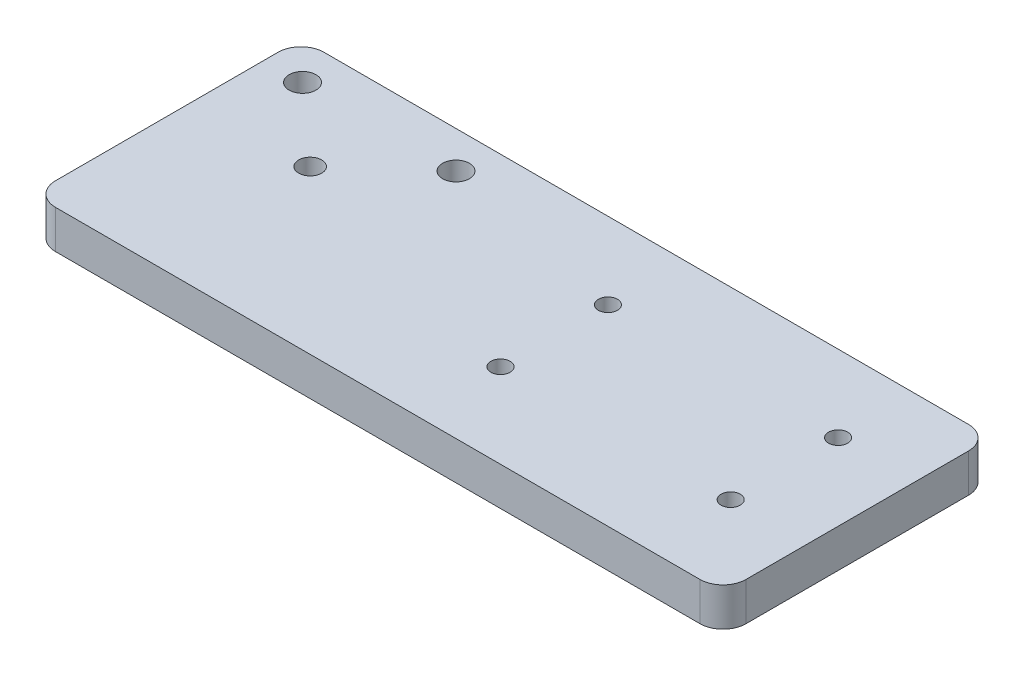
SolidWorks part; units mm, degrees
ref_plane "前视基准面" through (0, 0, 0) normal (0, 0, 1) x (1, 0, 0)
ref_plane "上视基准面" through (0, 0, 0) normal (0, 1, 0) x (1, 0, 0)
ref_plane "右视基准面" through (0, 0, 0) normal (1, 0, 0) x (0, 0, -1)
sketch "草图1" plane through (0, 0, 0) normal (0, 1, 0) x (1, 0, 0)
  line L1 (-45, 17.5) -> (45, 17.5)
  line L2 (-45, 17.5) -> (-45, -17.5)
  line L3 (-45, -17.5) -> (45, -17.5)
  line L4 (45, 17.5) -> (45, -17.5)
  line L5 (-45, 17.5) -> (45, -17.5) construction
  line L6 (-45, -17.5) -> (45, 17.5) construction
  point P0 (0, 0)
  dimension "D1" = 90
  dimension "D2" = 35
extrude "凸台-拉伸1" add sketch "草图1" along normal blind 5 contours L1 L4 L3 L2
sketch "草图2" plane through (0, 5, 0) normal (0, 1, 0) x (1, 0, 0)
  line L0 (45, 17.5) -> (45, -17.5) construction
  line L2 (-45, 17.5) -> (45, 17.5) construction
  circle A0 centre (35, 7.5) radius 1
  dimension "D1" = 2
  dimension "D3" = 10
  dimension "D2" = 10
extrude "切除-拉伸1" cut sketch "草图2" against normal through all
pattern_linear "阵列(线性)1" count 2 spacing 30 along (-1, 0, 0) count 2 spacing 14 along (0, 0, 1) of "切除-拉伸1"
sketch "草图3" plane through (0, 5, 0) normal (0, 1, 0) x (1, 0, 0)
  line L0 (20, 20.6257) -> (20, -26.9772) construction
  line L1 (-30, -26.9772) -> (-30, 24.2207) construction
  line L2 (-45, 17.5) -> (45, 17.5) construction
  circle A1 centre (35, 7.5) radius 1 construction
  circle A2 centre (-20, 12.7) radius 1.75
  dimension "D3" = 10
  dimension "D4" = 3.5
  dimension "D5" = 4.8
  dimension "D1" = 15
  dimension "D2" = 50
extrude "切除-拉伸2" cut sketch "草图3" against normal through all
pattern_linear "阵列(线性)2" count 2 spacing 20 along (-1, 0, 0) of "切除-拉伸2"
sketch "草图6" plane through (0, 5, 0) normal (0, 1, 0) x (1, 0, 0)
  circle A0 centre (-30, 3.7) radius 1.5
  circle A1 centre (-20, 12.7) radius 1.75 construction
  dimension "D1" = 3
  dimension "D2" = 9
  dimension "D3" = 10
extrude "切除-拉伸3" cut sketch "草图6" against normal through all
fillet "圆角1" radius 3 1 edges at (-45, 2.5, 17.5)
fillet "圆角2" radius 3 1 edges at (-45, 2.5, -17.5)
fillet "圆角3" radius 3 1 edges at (45, 2.5, -17.5)
fillet "圆角4" radius 3 1 edges at (45, 2.5, 17.5)
hole_wizard "M3 螺纹孔1" positions "草图7" profile "草图8" tap size "M3" standard "GB" end condition through all
sketch "草图7" plane through (0, 5, 0) normal (0, 1, 0) x (1, 0, 0)
  point P0 (5, 7.5)
  point P3 (5, -6.5)
  point P6 (35, 7.5)
  point P9 (35, -6.5)
sketch "草图8" plane through (5, 5, -7.5) normal (1, 0, 0) x (0, 0, 1)
  line L0 (0, 0) -> (0, 5)
  line L1 (0, 5) -> (1.25, 5)
  line L2 (1.25, 5) -> (1.25, 0)
  line L5 (1.25, 0) -> (0, 0)
  line L11 (0, -6.35) -> (0, 107.95) construction
  dimension "通孔螺纹孔钻头直径" = 2.5
  dimension "通孔螺纹孔钻头深度" = 5
cosmetic thread "孔螺蚊线1" parameters "D2"=3
cosmetic thread "孔螺蚊线2" parameters "D2"=3
cosmetic thread "孔螺蚊线3" parameters "D2"=3
cosmetic thread "孔螺蚊线4" parameters "D2"=3
